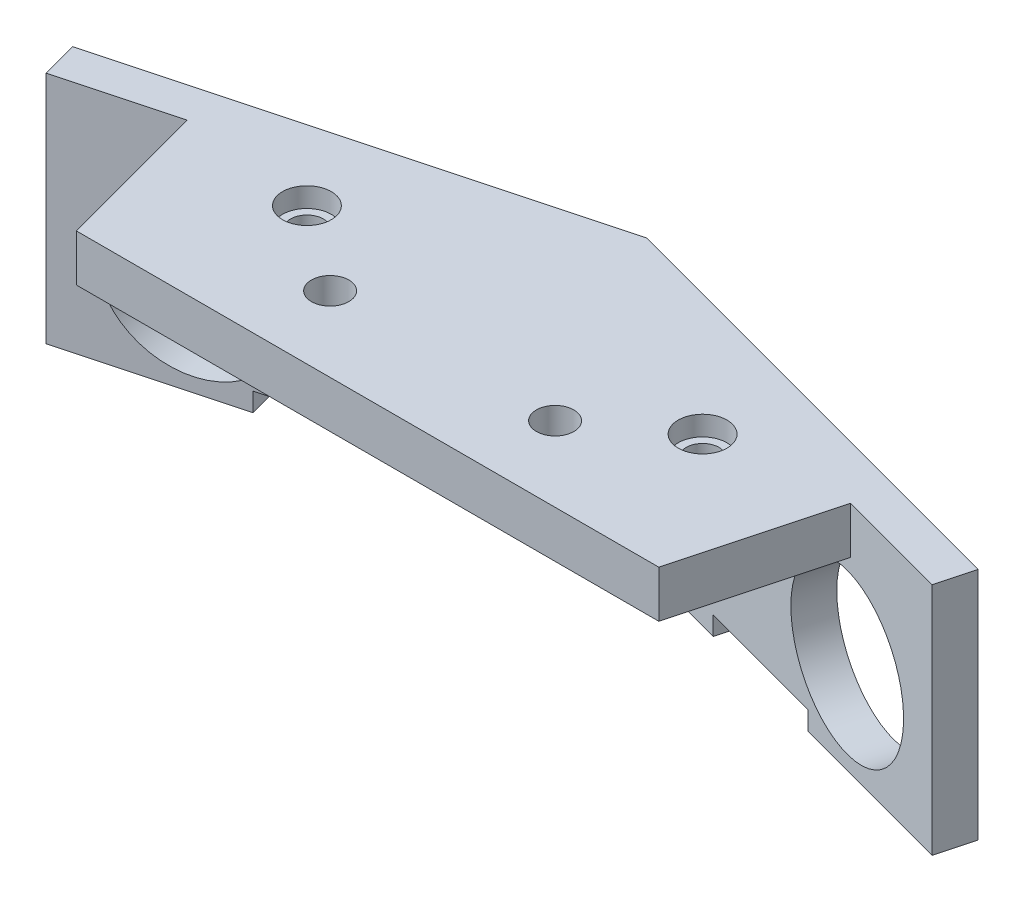
SolidWorks part; units mm, degrees
ref_plane "Front Plane" through (0, 0, 0) normal (0, 0, 1) x (1, 0, 0)
ref_plane "Top Plane" through (0, 0, 0) normal (0, 1, 0) x (1, 0, 0)
ref_plane "Right Plane" through (0, 0, 0) normal (1, 0, 0) x (0, 0, -1)
sketch "Sketch1" plane through (0, 0, 0) normal (0, 1, 0) x (1, 0, 0)
  line L0 (0, 0) -> (-48.2963, -12.941)
  line L1 (0, 0) -> (48.2963, -12.941)
  line L2 (0, 0) -> (0, 17.4877) construction
  line L3 (0, 0) -> (0, -21.1199) construction
  line L4 (-48.2963, -12.941) -> (-47.261, -16.8047)
  line L5 (-47.261, -16.8047) -> (0, -4.1411)
  line L8 (48.2963, -12.941) -> (47.261, -16.8047)
  line L9 (47.261, -16.8047) -> (0, -4.1411)
  dimension "D4" = 4
  dimension "D1" = 150
  dimension "D2" = 50
  dimension "D5" = 90
  dimension "D6" = 4
  dimension "D7" = 90
extrude "Boss-Extrude1" add sketch "Sketch1" along normal blind 25
sketch "Sketch2" plane through (0, 25, 0) normal (0, 1, 0) x (1, 0, 0)
  line L1 (0, -4.1411) -> (47.261, -16.8047) construction
  line L4 (18.8424, -29.7567) -> (-18.8424, -29.7567)
  line L7 (0, -29.7567) -> (0, 0) construction
  line L8 (0, -4.1411) -> (-35.3811, -13.6214)
  line L9 (35.3811, -13.6214) -> (31.0576, -29.7567)
  line L10 (31.0576, -29.7567) -> (18.8424, -29.7567)
  line L12 (-35.3811, -13.6214) -> (-31.0576, -29.7567)
  line L13 (-31.0576, -29.7567) -> (-18.8424, -29.7567)
  line L14 (35.3811, -13.6214) -> (0, -4.1411)
  circle A0 centre (-12, -21.7567) radius 2
  circle A1 centre (12, -21.7567) radius 2
  dimension "D3" = 4
  dimension "D4" = 4
  dimension "D1" = 8
  dimension "D5" = 24
  dimension "D6" = 12
extrude "Boss-Extrude2" add sketch "Sketch2" against normal blind 5
sketch "Sketch3" plane through (0, 25, 0) normal (0, 1, 0) x (1, 0, 0)
  line L0 (25.3451, -19.0075) -> (26.7168, -13.888)
  line L1 (26.7168, -13.888) -> (24.5918, -13.3186)
  line L2 (24.5918, -13.3186) -> (23.22, -18.4381)
  line L3 (23.22, -18.4381) -> (25.3451, -19.0075)
  line L4 (17.6177, -16.9369) -> (15.4926, -16.3675)
  line L5 (15.4926, -16.3675) -> (16.8644, -11.2481)
  line L6 (16.8644, -11.2481) -> (18.9894, -11.8175)
  line L7 (18.9894, -11.8175) -> (17.6177, -16.9369)
  line L8 (48.2963, -12.941) -> (0, 0) construction
  line L9 (31.0576, -29.7567) -> (35.3811, -13.6214) construction
  line L11 (0, 0) -> (0, -29.7567) construction
  line L12 (-31.0576, -29.7567) -> (31.0576, -29.7567) construction
  line L13 (15.4926, -16.3675) -> (17.6177, -16.9369)
  line L14 (18.9894, -11.8175) -> (16.8644, -11.2481)
  line L15 (24.5918, -13.3186) -> (26.7168, -13.888)
  line L16 (25.3451, -19.0075) -> (23.22, -18.4381)
  line L18 (-25.3451, -19.0075) -> (-23.22, -18.4381)
  line L19 (-24.5918, -13.3186) -> (-26.7168, -13.888)
  line L20 (-18.9894, -11.8175) -> (-16.8644, -11.2481)
  line L21 (-15.4926, -16.3675) -> (-17.6177, -16.9369)
  line L22 (-18.9894, -11.8175) -> (-17.6177, -16.9369)
  line L23 (-16.8644, -11.2481) -> (-18.9894, -11.8175)
  line L24 (-15.4926, -16.3675) -> (-16.8644, -11.2481)
  line L25 (-17.6177, -16.9369) -> (-15.4926, -16.3675)
  line L26 (-23.22, -18.4381) -> (-25.3451, -19.0075)
  line L27 (-24.5918, -13.3186) -> (-23.22, -18.4381)
  line L28 (-26.7168, -13.888) -> (-24.5918, -13.3186)
  line L29 (-25.3451, -19.0075) -> (-26.7168, -13.888)
  circle A0 centre (21.1047, -15.1278) radius 1.75
  circle A1 centre (-21.1047, -15.1278) radius 1.75
  dimension "D8" = 3.5
  dimension "D10" = 2.9
  dimension "D1" = 2.2
  dimension "D2" = 2.2
  dimension "D3" = 5.8
  dimension "D4" = 5.3
  dimension "D5" = 5.3
  dimension "D6" = 6.5
  dimension "D7" = 8.3
  dimension "D9" = 2.9
extrude "Cut-Extrude1" cut sketch "Sketch3" against normal blind 5 contours L2 L3 L0 L1 | A0 | L7 L6 L5 L4 | L21 L24 L20 L22 | A1 | L29 L18 L27 L19
sketch "Sketch4" plane through (0, 25, 0) normal (0, 1, 0) x (1, 0, 0)
  circle A1 centre (-21.1047, -15.1278) radius 2.6
  circle A2 centre (21.1047, -15.1278) radius 2.6
  dimension "D1" = 2.6
  dimension "D2" = 2.6
extrude "Cut-Extrude2" cut sketch "Sketch4" against normal blind 2.1
sketch "Sketch5" plane through (0, 25, 0) normal (0, 1, 0) x (1, 0, 0)
  line L0 (-26.7168, -13.888) -> (-25.3451, -19.0075)
  line L1 (-25.3451, -19.0075) -> (-23.22, -18.4381)
  line L2 (-23.22, -18.4381) -> (-24.5918, -13.3186)
  line L3 (-24.5918, -13.3186) -> (-26.7168, -13.888)
  line L4 (-17.6177, -16.9369) -> (-15.4926, -16.3675)
  line L5 (-15.4926, -16.3675) -> (-16.8644, -11.2481)
  line L6 (-16.8644, -11.2481) -> (-18.9894, -11.8175)
  line L7 (-18.9894, -11.8175) -> (-17.6177, -16.9369)
  line L8 (0, 0) -> (0, -29.7567) construction
  line L9 (-31.0576, -29.7567) -> (31.0576, -29.7567) construction
  line L10 (18.9894, -11.8175) -> (17.6177, -16.9369)
  line L11 (16.8644, -11.2481) -> (18.9894, -11.8175)
  line L12 (15.4926, -16.3675) -> (16.8644, -11.2481)
  line L13 (17.6177, -16.9369) -> (15.4926, -16.3675)
  line L14 (24.5918, -13.3186) -> (26.7168, -13.888)
  line L15 (23.22, -18.4381) -> (24.5918, -13.3186)
  line L16 (25.3451, -19.0075) -> (23.22, -18.4381)
  line L17 (26.7168, -13.888) -> (25.3451, -19.0075)
extrude "Boss-Extrude4" add sketch "Sketch5" against normal blind 1.5
sketch "Sketch6" plane through (0, 0, 0) normal (-0.2588, 0, -0.9659) x (-0.9659, 0, 0.2588)
  line L0 (0, 0) -> (50, 0) construction
  line L1 (50, 25) -> (50, 0) construction
  line L2 (0, 25) -> (0, 0) construction
  line L3 (0, 25) -> (50, 25) construction
  line L4 (30, 16.2) -> (19, 16.2)
  line L5 (30, 16.2) -> (30, 19.2)
  line L6 (30, 19.2) -> (19, 19.2)
  line L7 (19, 16.2) -> (19, 19.2)
  line L8 (30, 16.2) -> (19, 19.2) construction
  line L9 (30, 19.2) -> (19, 16.2) construction
  line L10 (30, 16.2) -> (19, 16.2)
  circle A0 centre (37.2, 10) radius 8.5
  circle A1 centre (11.2, 10) radius 8.5
  point P10 (24.5, 17.7)
  dimension "D1" = 10
  dimension "D3" = 17
  dimension "D4" = 17
  dimension "D2" = 10
  dimension "D5" = 12.8
  dimension "D6" = 11.2
  dimension "D7" = 3
  dimension "D8" = 11
  dimension "D9" = 8.8
  dimension "D10" = 31
extrude "Cut-Extrude3" cut sketch "Sketch6" against normal through all contours A0 | A1 | L7 L4 L5 L6
sketch "Sketch7" plane through (0, 0, 0) normal (0.2588, 0, -0.9659) x (-0.9659, 0, -0.2588)
  line L0 (-50, 0) -> (0, 0) construction
  line L1 (-50, 25) -> (-50, 0) construction
  line L2 (0, 25) -> (0, 0) construction
  line L4 (-18.5, 15.2) -> (-29.5, 15.2)
  line L5 (-18.5, 15.2) -> (-18.5, 19.2)
  line L6 (-18.5, 19.2) -> (-29.5, 19.2)
  line L7 (-29.5, 15.2) -> (-29.5, 19.2)
  line L8 (-18.5, 15.2) -> (-29.5, 19.2) construction
  line L9 (-18.5, 19.2) -> (-29.5, 15.2) construction
  line L10 (-50, 25) -> (0, 25) construction
  circle A0 centre (-10.82, 10) radius 8.5
  circle A1 centre (-37.2, 10) radius 8.5
  point P10 (-24, 17.2)
  dimension "D1" = 17
  dimension "D2" = 17
  dimension "D3" = 10
  dimension "D4" = 10
  dimension "D5" = 12.8
  dimension "D6" = 10.82
  dimension "D7" = 4
  dimension "D8" = 11
  dimension "D9" = 5.8
  dimension "D10" = 20.5
extrude "Cut-Extrude4" cut sketch "Sketch7" against normal through all
sketch "Sketch8" plane through (0, 0, 0) normal (0, -1, 0) x (-1, 0, 0)
  line L1 (-47.261, -16.8047) -> (-48.2963, -12.941) construction
  line L2 (0, -4.1411) -> (-47.261, -16.8047) construction
  line L3 (-29.1679, -11.9566) -> (-15.3638, -8.2578)
  line L4 (-35.3811, -13.6214) -> (0, -4.1411) construction
  line L7 (15.3638, -8.2578) -> (29.8527, -12.1401)
  line L8 (0, 0) -> (0, 16.5138) construction
  line L13 (-29.1679, -11.9566) -> (-29.8149, -9.5418)
  line L14 (-29.8149, -9.5418) -> (-16.0108, -5.843)
  line L15 (-16.0108, -5.843) -> (-15.3638, -8.2578)
  line L16 (15.3638, -8.2578) -> (16.0108, -5.843)
  line L19 (0, -4.1411) -> (35.3811, -13.6214) construction
  line L20 (29.8527, -12.1401) -> (30.4997, -9.7253)
  line L21 (16.0108, -5.843) -> (30.4997, -9.7253)
  dimension "D1" = 90
  dimension "D2" = 90
  dimension "D3" = 2.5
  dimension "D4" = 2.5
  dimension "D5" = 14.291
  dimension "D6" = 33.0224
  dimension "D7" = 15
  dimension "D8" = 2.5
  dimension "D9" = 2.5
extrude "Cut-Extrude6" cut sketch "Sketch8" against normal blind 2
sketch "Sketch9" plane through (0, 20, 0) normal (0, -1, 0) x (-1, 0, 0)
  line L0 (-17.6177, -16.9369) -> (-15.4926, -16.3675)
  line L1 (-25.3451, -19.0075) -> (-25.0863, -19.9734)
  line L2 (-25.0863, -19.9734) -> (-22.9612, -19.404)
  line L3 (-22.9612, -19.404) -> (-23.22, -18.4381)
  line L6 (-21.1047, -15.1278) -> (-20.1609, -18.6504) construction
  line L7 (-23.22, -18.4381) -> (-25.3451, -19.0075)
  line L8 (-17.3589, -17.9028) -> (-17.6177, -16.9369)
  line L9 (-15.2338, -17.3334) -> (-17.3589, -17.9028)
  line L10 (-15.4926, -16.3675) -> (-15.2338, -17.3334)
  line L11 (0, 0) -> (0, 7.4426) construction
  line L12 (-25.3451, -19.0075) -> (-25.0863, -19.9734)
  line L13 (-25.0863, -19.9734) -> (-22.9612, -19.404)
  line L14 (-22.9612, -19.404) -> (-23.22, -18.4381)
  line L15 (-17.6177, -16.9369) -> (-15.4926, -16.3675)
  line L16 (-17.3589, -17.9028) -> (-17.6177, -16.9369)
  line L17 (-15.2338, -17.3334) -> (-17.3589, -17.9028)
  line L18 (-15.4926, -16.3675) -> (-15.2338, -17.3334)
  line L19 (-23.22, -18.4381) -> (-25.3451, -19.0075)
  line L20 (21.1047, -15.1278) -> (20.1609, -18.6504) construction
  line L21 (23.22, -18.4381) -> (25.3451, -19.0075)
  line L22 (15.4926, -16.3675) -> (15.2338, -17.3334)
  line L23 (15.2338, -17.3334) -> (17.3589, -17.9028)
  line L24 (17.3589, -17.9028) -> (17.6177, -16.9369)
  line L25 (17.6177, -16.9369) -> (15.4926, -16.3675)
  line L26 (22.9612, -19.404) -> (23.22, -18.4381)
  line L27 (25.0863, -19.9734) -> (22.9612, -19.404)
  line L28 (25.3451, -19.0075) -> (25.0863, -19.9734)
  line L29 (15.4926, -16.3675) -> (15.2338, -17.3334)
  line L30 (15.2338, -17.3334) -> (17.3589, -17.9028)
  line L31 (17.3589, -17.9028) -> (17.6177, -16.9369)
  line L32 (23.22, -18.4381) -> (25.3451, -19.0075)
  line L33 (22.9612, -19.404) -> (23.22, -18.4381)
  line L34 (25.0863, -19.9734) -> (22.9612, -19.404)
  line L35 (25.3451, -19.0075) -> (25.0863, -19.9734)
  line L36 (17.6177, -16.9369) -> (15.4926, -16.3675)
  line M8 (-23.22, -18.4381) -> (-25.3451, -19.0075)
  line M14 (25.3451, -19.0075) -> (23.22, -18.4381)
  line M25 (17.6177, -16.9369) -> (15.4926, -16.3675)
  line M28 (-15.4926, -16.3675) -> (-17.6177, -16.9369)
  dimension "D1" = 2.2
  dimension "D2" = 1
  dimension "D3" = 90
extrude "Cut-Extrude7" cut sketch "Sketch9" against normal blind 3.5 contours L2 L3 L1 M8 | L10 L8 L9 M28 | L23 L24 L22 M25 | L28 L26 L27 M14
